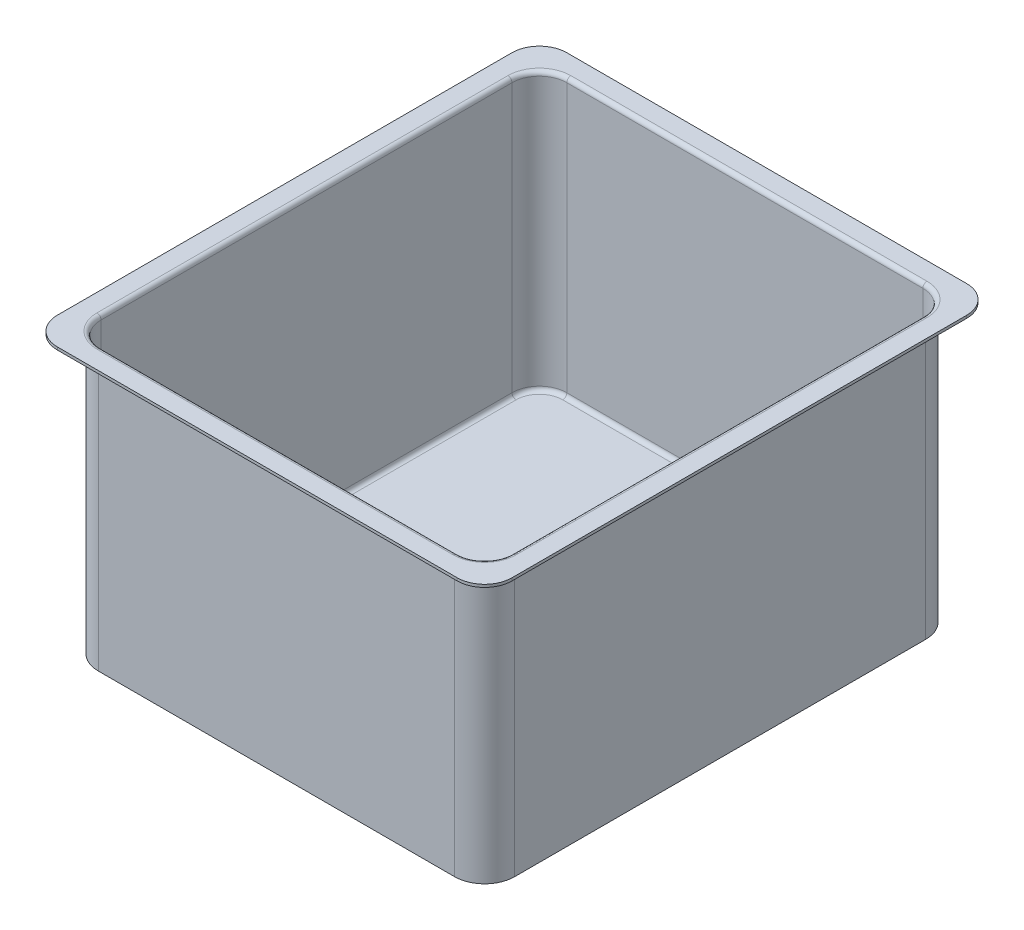
SolidWorks part; units mm, degrees
ref_plane "Front Plane" through (0, 0, 0) normal (0, 0, 1) x (1, 0, 0)
ref_plane "Top Plane" through (0, 0, 0) normal (0, 1, 0) x (1, 0, 0)
ref_plane "Right Plane" through (0, 0, 0) normal (1, 0, 0) x (0, 0, -1)
sketch "Sketch1" plane through (0, 0, 0) normal (0, 1, 0) x (1, 0, 0)
  line L1 (-146, 186) -> (146, 186)
  line L2 (-166, 166) -> (-166, -166)
  line L3 (-146, -186) -> (146, -186)
  line L4 (166, 166) -> (166, -166)
  line L5 (-166, 186) -> (166, -186) construction
  line L6 (-166, -186) -> (166, 186) construction
  arc A0 (-166, -166) -> (-146, -186) centre (-146, -166) ccw
  arc A1 (146, -186) -> (166, -166) centre (146, -166) ccw
  arc A2 (146, 186) -> (166, 166) centre (146, 166) cw
  arc A3 (-146, 186) -> (-166, 166) centre (-146, 166) ccw
  point P0 (0, 0)
  dimension "D3" = 20
  dimension "D1" = 332
  dimension "D2" = 372
extrude "Boss-Extrude1" add sketch "Sketch1" along normal blind 2
sketch "Sketch2" plane through (0, 2, 0) normal (0, 1, 0) x (1, 0, 0)
  line L1 (-130, 170) -> (130, 170)
  line L2 (-150, 150) -> (-150, -150)
  line L3 (-130, -170) -> (130, -170)
  line L4 (150, 150) -> (150, -150)
  line L5 (-150, 170) -> (150, -170) construction
  line L6 (-150, -170) -> (150, 170) construction
  arc A0 (-150, -150) -> (-130, -170) centre (-130, -150) ccw
  arc A1 (130, -170) -> (150, -150) centre (130, -150) ccw
  arc A2 (130, 170) -> (150, 150) centre (130, 150) cw
  arc A3 (-130, 170) -> (-150, 150) centre (-130, 150) ccw
  point P0 (0, 0)
  dimension "D3" = 20
  dimension "D1" = 340
  dimension "D2" = 300
extrude "Cut-Extrude1" cut sketch "Sketch2" against normal up to next
sketch "Sketch3" plane through (0, 0, 0) normal (0, -1, 0) x (1, 0, 0)
  line L0 (150, -150) -> (150, 150) construction
  line L1 (-130, 170) -> (130, 170)
  line L2 (-150, 150) -> (-150, -150)
  line L3 (-130, -170) -> (130, -170)
  line L4 (150, 150) -> (150, -150)
  line L5 (-150, 170) -> (150, -170) construction
  line L6 (-150, -170) -> (150, 170) construction
  line L7 (-130, -170) -> (130, -170) construction
  line L8 (-152, 150) -> (-152, -150)
  line L9 (-130, -172) -> (130, -172)
  line L10 (152, 150) -> (152, -150)
  line L11 (-130, 172) -> (130, 172)
  arc A0 (-150, -150) -> (-130, -170) centre (-130, -150) ccw
  arc A1 (130, -170) -> (150, -150) centre (130, -150) ccw
  arc A2 (130, 170) -> (150, 150) centre (130, 150) cw
  arc A3 (-130, 170) -> (-150, 150) centre (-130, 150) ccw
  arc A4 (-152, -150) -> (-130, -172) centre (-130, -150) ccw
  arc A5 (130, -172) -> (152, -150) centre (130, -150) ccw
  arc A6 (130, 172) -> (152, 150) centre (130, 150) cw
  arc A7 (-130, 172) -> (-152, 150) centre (-130, 150) ccw
  point P0 (0, 0)
  dimension "D1" = 20
  dimension "D2" = 2
extrude "Boss-Extrude2" add sketch "Sketch3" along normal blind 200
sketch "Sketch4" plane through (0, -200, 0) normal (0, -1, 0) x (1, 0, 0)
  line L0 (152, -150) -> (152, 150) construction
  line L1 (-130, 172) -> (130, 172)
  line L2 (-152, 150) -> (-152, -150)
  line L3 (-130, -172) -> (130, -172)
  line L4 (152, 150) -> (152, -150)
  line L5 (-152, 172) -> (152, -172) construction
  line L6 (-152, -172) -> (152, 172) construction
  line L7 (-130, -172) -> (130, -172) construction
  arc A0 (130, 172) -> (152, 150) centre (130, 150) cw
  arc A1 (-130, 172) -> (-152, 150) centre (-130, 150) ccw
  arc A2 (130, -172) -> (152, -150) centre (130, -150) ccw
  arc A3 (-152, -150) -> (-130, -172) centre (-130, -150) ccw
  point P0 (0, 0)
  dimension "D1" = 22
extrude "Boss-Extrude3" add sketch "Sketch4" along normal blind 2
fillet "Fillet1" radius 3 16 edges at (-144.1421, -200, 164.1421) (0, -200, 170) (144.1421, -200, 164.1421) (150, -200, 0) (144.1421, -200, -164.1421) (0, -200, -170) (-144.1421, -200, -164.1421) (-144.1421, 2, 164.1421) (-150, 2, 0) (-144.1421, 2, -164.1421) (0, 2, -170) (144.1421, 2, -164.1421) (150, 2, 0) (144.1421, 2, 164.1421) (-150, -200, 0) (0, 2, 170)
